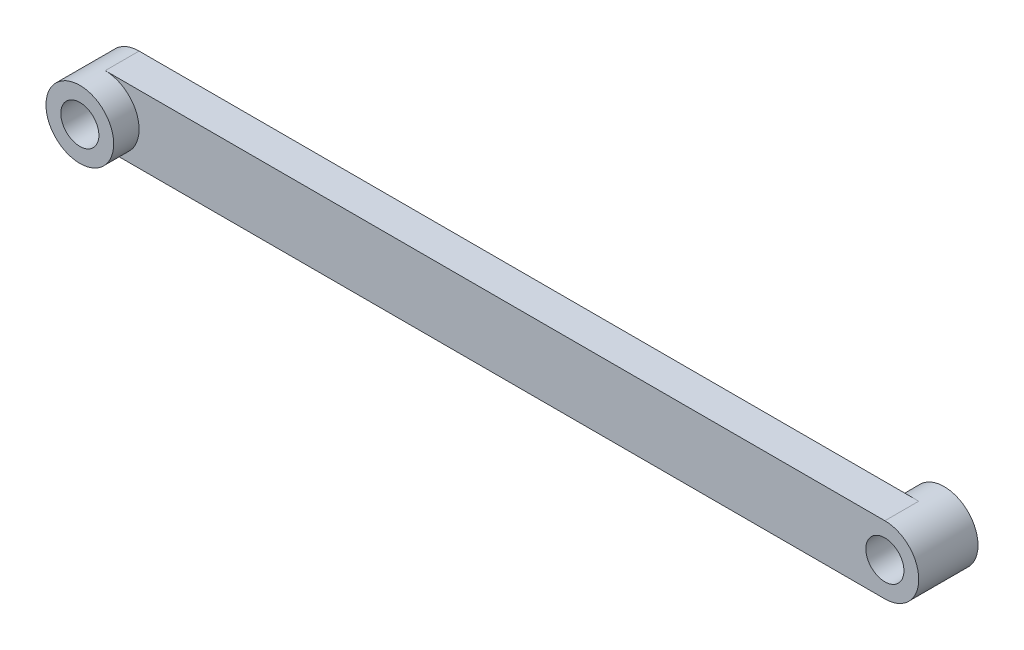
SolidWorks part; units mm, degrees
ref_plane "Front Plane" through (0, 0, 0) normal (0, 0, 1) x (1, 0, 0)
ref_plane "Top Plane" through (0, 0, 0) normal (0, 1, 0) x (1, 0, 0)
ref_plane "Right Plane" through (0, 0, 0) normal (1, 0, 0) x (0, 0, -1)
sketch "Sketch2" plane through (0, 0, 0) normal (0, 0, 1) x (1, 0, 0)
  line L0 (0, 0) -> (0, 13096.6669) construction
  line L1 (0, 0) -> (13096.6669, 0) construction
  line L2 (0, 4) -> (92.1, 4)
  line L3 (0, -4) -> (92.1, -4)
  circle A0 centre (0, 0) radius 2.25
  circle A1 centre (92.1, 0) radius 2.25
  arc A2 (0, 4) -> (0, -4) centre (0, 0) ccw
  arc A3 (92.1, -4) -> (92.1, 4) centre (92.1, 0) ccw
  dimension "D1" = 4.5
  dimension "D3" = 8
  dimension "D2" = 92.1
extrude "Boss-Extrude1" add sketch "Sketch2" along normal blind 10
sketch "Sketch3" plane through (0, 0, 10) normal (0, 0, 1) x (1, 0, 0)
  circle A0 centre (0, 0) radius 4
extrude "Cut-Extrude-Thin1" cut sketch "Sketch3" against normal blind 3 thin
sketch "Sketch4" plane through (0, 0, 0) normal (0, 0, -1) x (-1, 0, 0)
  circle A0 centre (-92.1, 0) radius 4
extrude "Cut-Extrude-Thin2" cut sketch "Sketch4" against normal blind 3 thin
